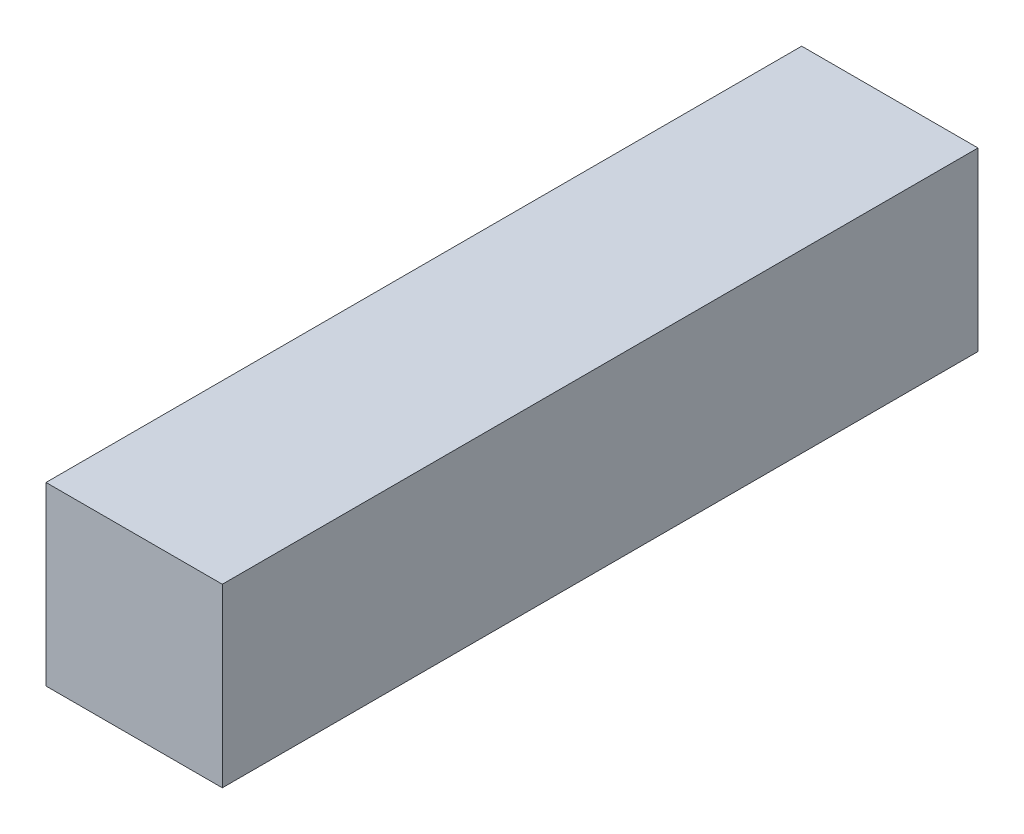
SolidWorks part; units mm, degrees
ref_plane "Front Plane" through (0, 0, 0) normal (0, 0, 1) x (1, 0, 0)
ref_plane "Top Plane" through (0, 0, 0) normal (0, 1, 0) x (1, 0, 0)
ref_plane "Right Plane" through (0, 0, 0) normal (1, 0, 0) x (0, 0, -1)
sketch "Sketch1" plane through (0, 0, 0) normal (0, 0, 1) x (1, 0, 0)
  line L1 (0, 0) -> (2.8, 0)
  line L2 (0, 0) -> (0, 2.8)
  line L3 (0, 2.8) -> (2.8, 2.8)
  line L4 (2.8, 0) -> (2.8, 2.8)
  dimension "D1" = 2.8
extrude "Boss-Extrude1" add sketch "Sketch1" along normal blind 12
